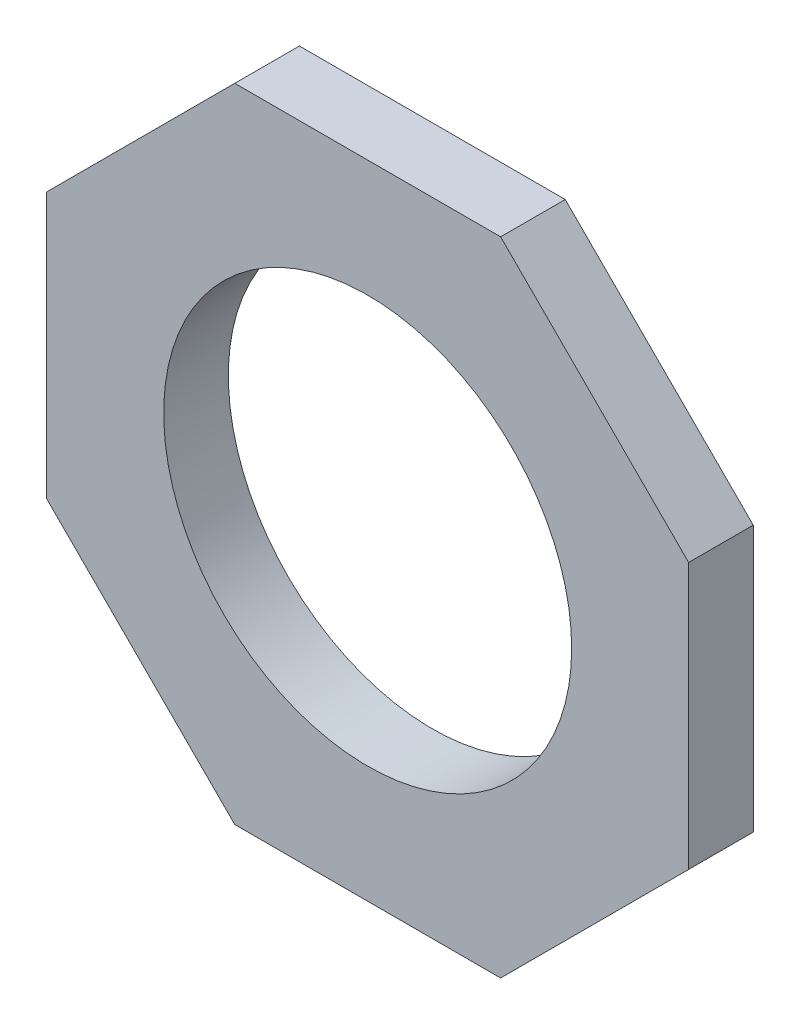
SolidWorks part; units mm, degrees
ref_plane "Front Plane" through (0, 0, 0) normal (0, 0, 1) x (1, 0, 0)
ref_plane "Top Plane" through (0, 0, 0) normal (0, 1, 0) x (1, 0, 0)
ref_plane "Right Plane" through (0, 0, 0) normal (1, 0, 0) x (0, 0, -1)
sketch "Sketch1" plane through (0, 0, 0) normal (0, 0, 1) x (1, 0, 0)
  line L3 (-3.2911, 7.9454) -> (3.2911, 7.9454)
  line L4 (3.2911, 7.9454) -> (7.9454, 3.2911)
  line L5 (7.9454, 3.2911) -> (7.9454, -3.2911)
  line L6 (7.9454, -3.2911) -> (3.2911, -7.9454)
  line L7 (3.2911, -7.9454) -> (-3.2911, -7.9454)
  line L8 (-3.2911, -7.9454) -> (-7.9454, -3.2911)
  line L9 (-7.9454, -3.2911) -> (-7.9454, 3.2911)
  line L10 (-7.9454, 3.2911) -> (-3.2911, 7.9454)
  circle A1 centre (0, 0) radius 5.05
  circle A2 centre (0, 0) radius 8.6 construction
  dimension "D1" = 17.2
  dimension "D4" = 10.1
extrude "Boss-Extrude1" add sketch "Sketch1" along normal blind 1.6
